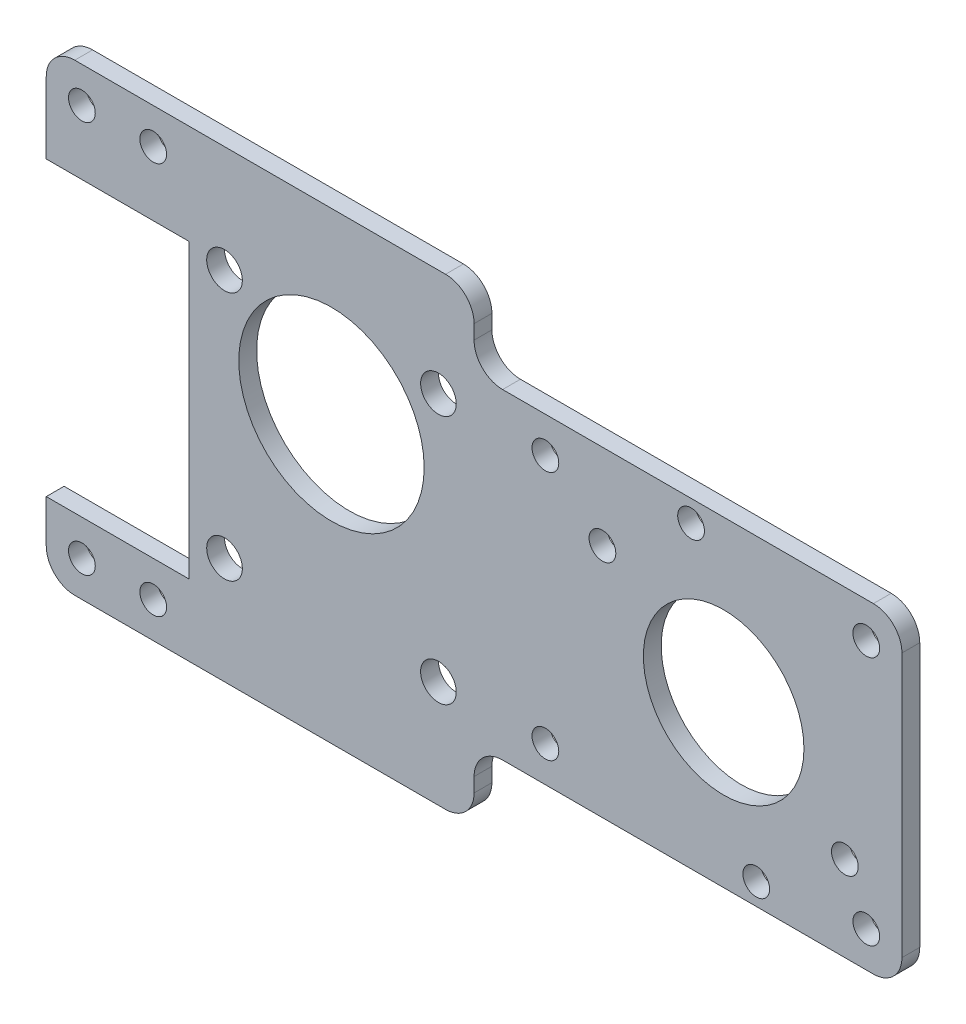
SolidWorks part; units mm, degrees
material "6061-T6 (SS)"
ref_plane "Front Plane" through (0, 0, 0) normal (0, 0, 1) x (1, 0, 0)
ref_plane "Top Plane" through (0, 0, 0) normal (0, 1, 0) x (1, 0, 0)
ref_plane "Right Plane" through (0, 0, 0) normal (1, 0, 0) x (0, 0, -1)
sketch "Sketch1" plane through (0, 0, 0) normal (0, 0, 1) x (1, 0, 0)
  line L1 (-63.5, 28.575) -> (63.5, 28.575)
  line L2 (-63.5, 28.575) -> (-63.5, -28.575)
  line L3 (-63.5, -28.575) -> (63.5, -28.575)
  line L4 (63.5, 28.575) -> (63.5, -28.575)
  line L5 (-63.5, 28.575) -> (63.5, -28.575) construction
  line L6 (-63.5, -28.575) -> (63.5, 28.575) construction
  circle A0 centre (31.75, 0) radius 14.3002
  circle A1 centre (31.75, 0) radius 25.4 construction
  circle A2 centre (37.5551, -24.7277) radius 2.3812
  circle A3 centre (18.3697, -21.59) radius 2.3813
  circle A4 centre (7.0223, -5.8051) radius 2.3813
  circle A5 centre (10.16, 13.3803) radius 2.3813
  circle A6 centre (25.9449, 24.7277) radius 2.3813
  circle A7 centre (45.1303, 21.59) radius 2.3812
  circle A8 centre (56.4777, 5.8051) radius 2.3812
  circle A9 centre (53.34, -13.3803) radius 2.3812
  point P0 (0, 0)
  point P27 (31.75, 0)
  dimension "D3" = 28.6004
  dimension "D5" = 50.8
  dimension "D8" = 4.7625
  dimension "D1" = 127
  dimension "D2" = 57.15
  dimension "D4" = 31.75
  dimension "D7" = 21.59
  dimension "D6" = 8
extrude "Boss-Extrude1" add sketch "Sketch1" along normal blind 3.175 contours A8 L4 L1 L2 L3 A9 A7 A6 A5 A4 A3 A2 A0 | L4 A8 | A3 | A4 | A7
sketch "Sketch2" plane through (0, 0, 3.175) normal (0, 0, 1) x (1, 0, 0)
  line L0 (-63.5, 28.575) -> (63.5, 28.575) construction
  line L1 (63.5, 28.575) -> (63.5, -28.575) construction
  line L2 (-63.5, -28.575) -> (63.5, -28.575) construction
  circle A0 centre (57.15, 22.225) radius 2.3812
  circle A1 centre (57.15, -22.225) radius 2.3812
  circle A2 centre (0, 22.225) radius 2.3813
  circle A3 centre (0, -22.225) radius 2.3813
  dimension "D1" = 4.7625
  dimension "D4" = 4.7625
  dimension "D7" = 4.7625
  dimension "D8" = 4.7625
  dimension "D2" = 6.35
  dimension "D3" = 6.35
  dimension "D5" = 6.35
  dimension "D6" = 6.35
  dimension "D9" = 57.15
  dimension "D10" = 57.15
  dimension "D11" = 6.35
  dimension "D12" = 6.35
extrude "Cut-Extrude1" cut sketch "Sketch2" against normal blind 3.175
fillet "Fillet1" radius 5.08 2 edges at (63.5, -28.575, 1.5875) (63.5, 28.575, 1.5875)
sketch "Sketch3" plane through (0, 0, 3.175) normal (0, 0, 1) x (1, 0, 0)
  line L0 (-63.5, 28.575) -> (-63.5, -28.575) construction
  line L1 (-63.5, 28.575) -> (58.42, 28.575) construction
  line L2 (-63.5, 0) -> (63.5, 0) construction
  line L3 (63.5, 23.495) -> (63.5, -23.495) construction
  circle A0 centre (-57.15, 22.225) radius 3.175
  circle A1 centre (-19.05, 22.225) radius 3.175
  circle A2 centre (-19.05, -22.225) radius 3.175
  circle A3 centre (-57.15, -22.225) radius 3.175
  dimension "D3" = 6.35
  dimension "D4" = 6.35
  dimension "D1" = 6.35
  dimension "D2" = 6.35
  dimension "D5" = 38.1
extrude "Cut-Extrude2" cut sketch "Sketch3" against normal blind 3.175
sketch "Sketch4" plane through (0, 0, 3.175) normal (0, 0, 1) x (1, 0, 0)
  line L0 (-63.5, 28.575) -> (58.42, 28.575) construction
  line L1 (-63.5, 28.575) -> (-63.5, -28.575) construction
  circle A0 centre (-38.1, 9.525) radius 16.51
  dimension "D1" = 33.02
  dimension "D2" = 19.05
  dimension "D3" = 25.4
extrude "Cut-Extrude3" cut sketch "Sketch4" against normal blind 7.62
sketch "Sketch5" plane through (0, 0, 3.175) normal (0, 0, 1) x (1, 0, 0)
  line L0 (-63.5, -28.575) -> (58.42, -28.575) construction
  line L1 (-12.7, -28.575) -> (-88.9, -28.575)
  line L2 (-12.7, -28.575) -> (-12.7, -41.275)
  line L3 (-12.7, -41.275) -> (-88.9, -41.275)
  line L4 (-88.9, -28.575) -> (-88.9, -41.275)
  line L5 (-63.5, 28.575) -> (-63.5, -28.575) construction
  line L6 (-63.5, 28.575) -> (58.42, 28.575) construction
  line L7 (-12.7, 28.575) -> (-88.9, 28.575)
  line L8 (-12.7, 28.575) -> (-12.7, 41.275)
  line L9 (-12.7, 41.275) -> (-88.9, 41.275)
  line L10 (-88.9, 28.575) -> (-88.9, 41.275)
  dimension "D1" = 50.8
  dimension "D2" = 12.7
  dimension "D3" = 25.4
  dimension "D4" = 12.7
  dimension "D5" = 25.4
  dimension "D6" = 50.8
extrude "Boss-Extrude2" add sketch "Sketch5" against normal blind 3.175
fillet "Fillet2" radius 5.08 4 edges at (-12.7, -41.275, 1.5875) (-12.7, -28.575, 1.5875) (-12.7, 41.275, 1.5875) (-12.7, 28.575, 1.5875)
sketch "Sketch6" plane through (0, 0, 3.175) normal (0, 0, 1) x (1, 0, 0)
  line L0 (-88.9, 41.275) -> (-88.9, 28.575) construction
  line L1 (-63.5, 28.575) -> (-88.9, 28.575)
  line L2 (-63.5, 28.575) -> (-63.5, 23.495)
  line L3 (-63.5, 23.495) -> (-88.9, 23.495)
  line L4 (-88.9, 28.575) -> (-88.9, 23.495)
  line L5 (-63.5, -28.575) -> (-88.9, -28.575) construction
  dimension "D1" = 52.07
extrude "Boss-Extrude3" add sketch "Sketch6" against normal blind 3.175
fillet "Fillet3" radius 5.08 2 edges at (-88.9, 41.275, 1.5875) (-88.9, -41.275, 1.5875)
sketch "Sketch7" plane through (0, 0, 3.175) normal (0, 0, 1) x (1, 0, 0)
  line L0 (-88.9, -28.575) -> (-88.9, -36.195) construction
  line L1 (-88.9, 36.195) -> (-88.9, 23.495) construction
  line L2 (-83.82, -41.275) -> (-17.78, -41.275) construction
  line L3 (-17.78, 41.275) -> (-83.82, 41.275) construction
  line L4 (-17.78, 41.275) -> (-83.82, 41.275) construction
  circle A0 centre (-82.55, 34.925) radius 2.3813
  circle A1 centre (-82.55, -34.925) radius 2.3813
  circle A2 centre (-69.85, 34.925) radius 2.3813
  circle A3 centre (-69.85, -34.925) radius 2.3813
  dimension "D1" = 4.7625
  dimension "D2" = 4.7625
  dimension "D7" = 4.7625
  dimension "D8" = 4.7625
  dimension "D3" = 6.35
  dimension "D4" = 6.35
  dimension "D5" = 6.35
  dimension "D6" = 6.35
  dimension "D9" = 6.35
  dimension "D10" = 6.35
  dimension "D11" = 12.7
  dimension "D12" = 12.7
extrude "Cut-Extrude4" cut sketch "Sketch7" against normal blind 3.175
